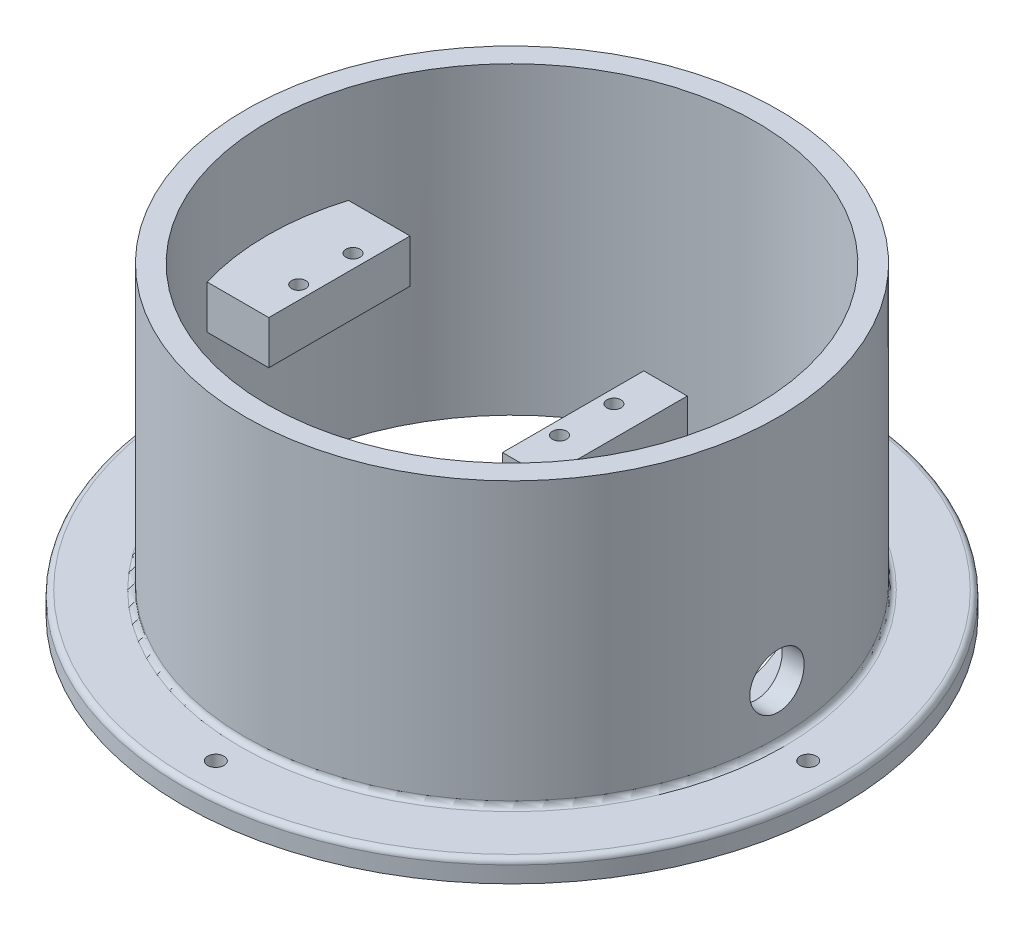
SolidWorks part; units mm, degrees
ref_plane "Front Plane" through (0, 0, 0) normal (0, 0, 1) x (1, 0, 0)
ref_plane "Top Plane" through (0, 0, 0) normal (0, 1, 0) x (1, 0, 0)
ref_plane "Right Plane" through (0, 0, 0) normal (1, 0, 0) x (0, 0, -1)
sketch "Sketch1" plane through (0, 0, 0) normal (0, 1, 0) x (1, 0, 0)
  circle A0 centre (0, 0) radius 45
  circle A1 centre (0, 0) radius 60.625
  dimension "D1" = 90
  dimension "D2" = 121.25
extrude "Boss-Extrude2" add sketch "Sketch1" along normal blind 4
sketch "Sketch2" plane through (0, 4, 0) normal (0, 1, 0) x (1, 0, 0)
  circle A0 centre (0, 0) radius 45
  circle A1 centre (0, 0) radius 49
  dimension "D1" = 90
  dimension "D2" = 98
extrude "Boss-Extrude3" add sketch "Sketch2" along normal blind 52
sketch "Sketch3" plane through (0, 0, 0) normal (0, 0, 1) x (1, 0, 0)
  line L0 (45, 56) -> (-45, 56) construction
  line L1 (11.25, 0) -> (19.25, 0)
  line L2 (11.25, 0) -> (11.25, 38)
  line L3 (11.25, 38) -> (19.25, 38)
  line L4 (19.25, 0) -> (19.25, 38)
  line L5 (-46.75, 38) -> (-31.75, 38)
  line L6 (-46.75, 38) -> (-46.75, 30)
  line L7 (-46.75, 30) -> (-31.75, 30)
  line L8 (-31.75, 38) -> (-31.75, 30)
  dimension "D1" = 8
  dimension "D2" = 11.25
  dimension "D3" = 38
  dimension "D4" = 43
  dimension "D5" = 15
  dimension "D6" = 8
  dimension "D7" = 18
extrude "Boss-Extrude5" add sketch "Sketch3" along normal mid plane 26
sketch "Sketch4" plane through (11.25, 0, 0) normal (-1, 0, 0) x (0, 0, 1)
  line L0 (0, 0) -> (0, 56) construction
  line L1 (45, 56) -> (-45, 56) construction
  line L3 (-5, 29) -> (5, 29)
  line L4 (-5, 29) -> (-5, 5)
  line L5 (-5, 5) -> (5, 5)
  line L6 (5, 29) -> (5, 5)
  line L7 (-5, 29) -> (5, 5) construction
  line L8 (-5, 5) -> (5, 29) construction
  point P5 (0, 17)
  dimension "D1" = 5
  dimension "D2" = 24
  dimension "D3" = 10
extrude "Cut-Extrude1" cut sketch "Sketch4" against normal up to next (8 mm away)
sketch "Sketch5" plane through (11.25, 0, 0) normal (-1, 0, 0) x (0, 0, 1)
  line L0 (0, 0) -> (0, 56) construction
  line L1 (45, 56) -> (-45, 56) construction
  circle A0 centre (0, 14) radius 5
  dimension "D2" = 10
  dimension "D1" = 14
extrude "Cut-Extrude2" cut sketch "Sketch5" against normal through all
sketch "Sketch7" plane through (0, 38, 0) normal (0, 1, 0) x (1, 0, 0)
  line L0 (-45, 0) -> (45, 0) construction
  line L1 (-31.75, -13) -> (-31.75, 13) construction
  line L2 (-34.25, 5) -> (13.75, 5) construction
  line L3 (-34.25, 5) -> (-34.25, -5) construction
  line L4 (-34.25, -5) -> (13.75, -5) construction
  line L5 (13.75, 5) -> (13.75, -5) construction
  line L6 (11.25, -13) -> (11.25, 13) construction
  arc A0 (-43.0813, 13) -> (-43.0813, -13) centre (0, 0) ccw construction
  arc A1 (44.7214, -5) -> (44.7214, 5) centre (0, 0) ccw construction
  circle A2 centre (-34.25, 5) radius 1.3
  circle A3 centre (-34.25, -5) radius 1.3
  circle A4 centre (13.75, 5) radius 1.3
  circle A5 centre (13.75, -5) radius 1.3
  dimension "D5" = 2.6
  dimension "D1" = 5
  dimension "D2" = 5
  dimension "D3" = 2.5
  dimension "D4" = 2.5
extrude "Cut-Extrude3" cut sketch "Sketch7" against normal blind 7.2
sketch "Sketch8" plane through (0, 0, 0) normal (0, -1, 0) x (1, 0, 0)
  line L0 (11.25, 13) -> (25.2498, 37.2484)
  line L1 (19.25, 0) -> (67.7896, 0) construction
  line L2 (19.25, 13) -> (19.25, -13) construction
  line L3 (11.25, -13) -> (25.2498, -37.2484)
  line L4 (11.25, 13) -> (11.25, -13)
  line L5 (24.25, 19.5167) -> (27.3618, 24.9065)
  line L6 (24.25, -19.5167) -> (27.3618, -24.9065)
  line L8 (24.25, 19.5167) -> (24.25, -19.5167)
  line L9 (19.25, 10.8564) -> (27.3618, 24.9065) construction
  line L10 (19.25, 10.8564) -> (19.25, -10.8564) construction
  line L11 (19.25, -10.8564) -> (27.3618, -24.9065) construction
  circle A0 centre (0, 0) radius 45 construction
  arc A1 (25.2498, -37.2484) -> (25.2498, 37.2484) centre (0, 0) ccw
  arc A2 (27.3618, -24.9065) -> (27.3618, 24.9065) centre (0, 0) ccw
  dimension "D1" = 60
  dimension "D3" = 5
  dimension "D2" = 8
extrude "Boss-Extrude6" add sketch "Sketch8" against normal blind 4
sketch "Sketch9" plane through (0, 0, 0) normal (0, -1, 0) x (1, 0, 0)
  circle A0 centre (0, 0) radius 54.5 construction
  circle A1 centre (54.5, 0) radius 1.5
  circle A2 centre (0, -54.5) radius 1.5
  circle A3 centre (-54.5, 0) radius 1.5
  circle A4 centre (0, 54.5) radius 1.5
  dimension "D1" = 109
  dimension "D2" = 3
  dimension "D3" = 4
extrude "Cut-Extrude4" cut sketch "Sketch9" against normal through all
fillet "Fillet1" radius 1 2 edges at (0, 4, 60.625) (0, 4, 49)
